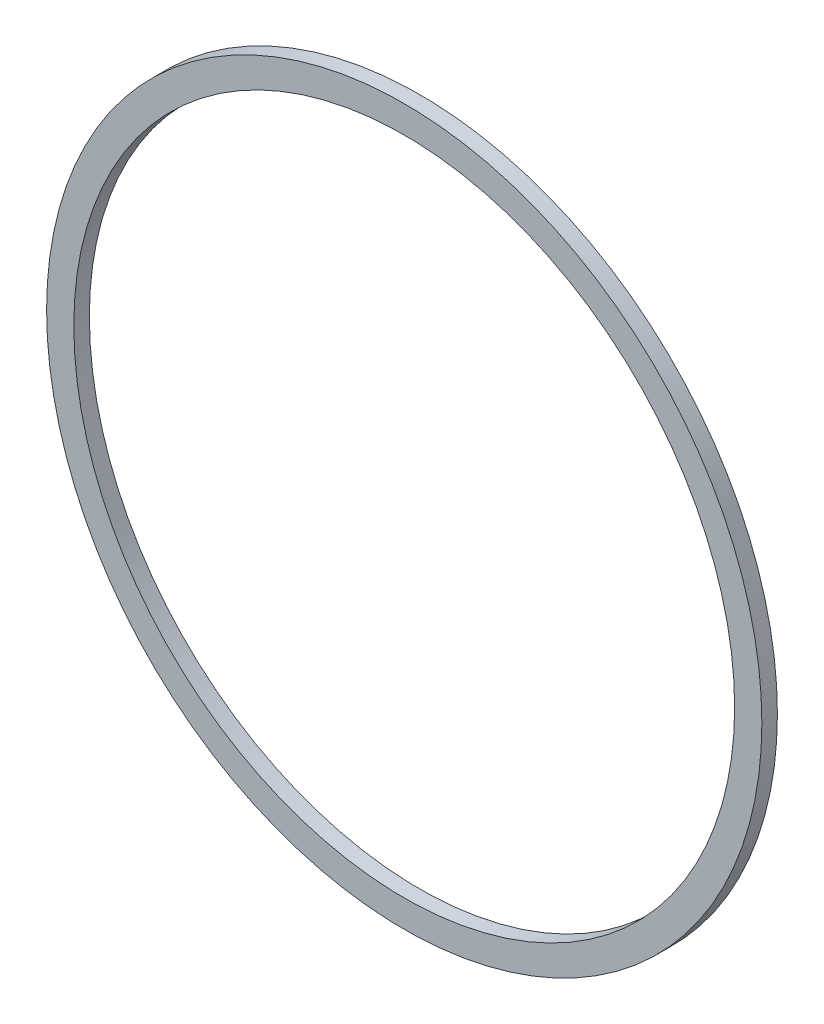
SolidWorks part; units mm, degrees
ref_plane "Front Plane" through (0, 0, 0) normal (0, 0, 1) x (1, 0, 0)
ref_plane "Top Plane" through (0, 0, 0) normal (0, 1, 0) x (1, 0, 0)
ref_plane "Right Plane" through (0, 0, 0) normal (1, 0, 0) x (0, 0, -1)
sketch "Sketch1" plane through (0, 0, 0) normal (0, 0, 1) x (1, 0, 0)
  circle A0 centre (0, 0) radius 42.5
  circle A1 centre (0, 0) radius 46
extrude "Boss-Extrude1" add sketch "Sketch1" against normal blind 2
